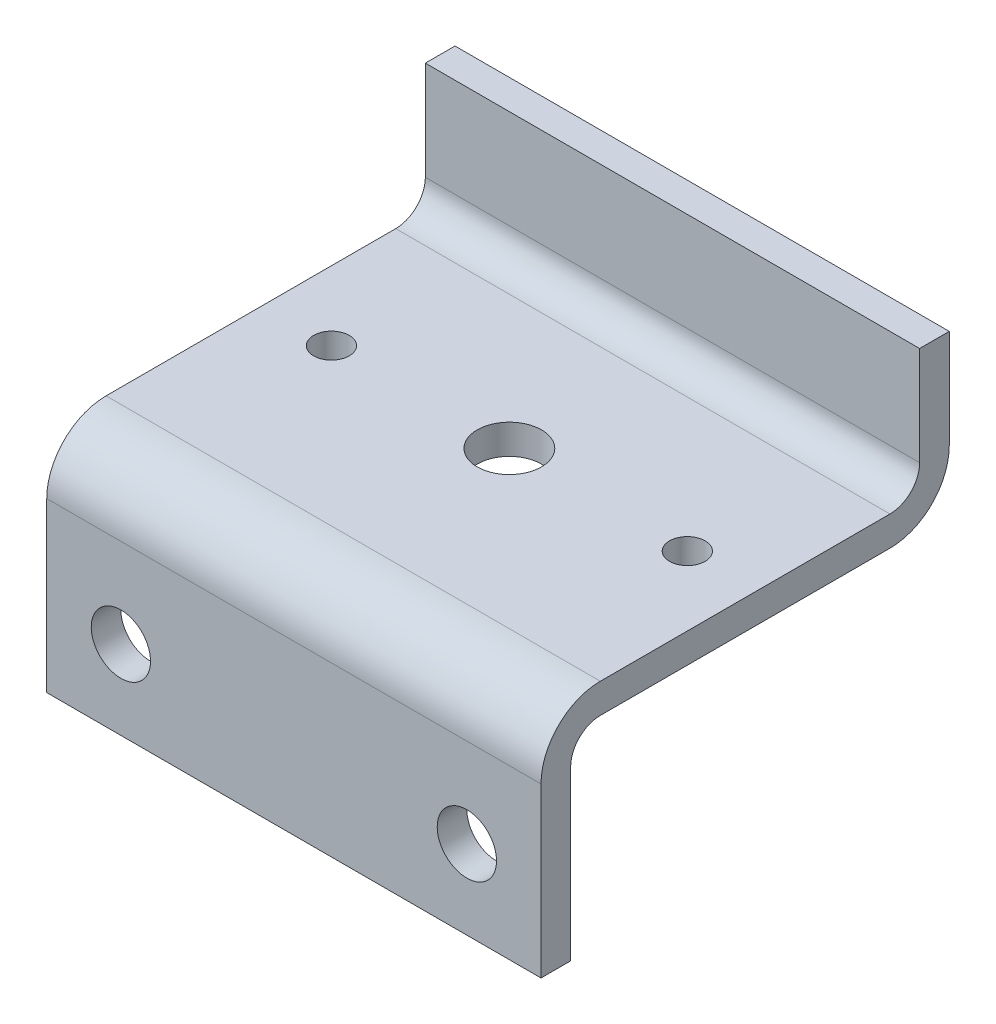
SolidWorks part; units mm, degrees
ref_plane "Front Plane" through (0, 0, 0) normal (0, 0, 1) x (1, 0, 0)
ref_plane "Top Plane" through (0, 0, 0) normal (0, 1, 0) x (1, 0, 0)
ref_plane "Right Plane" through (0, 0, 0) normal (1, 0, 0) x (0, 0, -1)
sketch "Sketch1" plane through (0, 0, 0) normal (1, 0, 0) x (0, 0, -1)
  line L0 (0, 0) -> (0, 17)
  line L1 (6, 23) -> (35.3, 23)
  line L4 (3, 17) -> (3, 0)
  line L5 (3, 0) -> (0, 0)
  line L6 (38.3, 26) -> (38.3, 36)
  line L7 (38.3, 36) -> (41.3, 36)
  line L8 (41.3, 36) -> (41.3, 26)
  line L9 (6, 20) -> (35.3, 20)
  arc A0 (6, 20) -> (3, 17) centre (6, 17) ccw
  arc A1 (0, 17) -> (6, 23) centre (6, 17) cw
  arc A2 (35.3, 23) -> (38.3, 26) centre (35.3, 26) ccw
  arc A3 (41.3, 26) -> (35.3, 20) centre (35.3, 26) cw
  point P11 (0, 23)
  point P16 (38.3, 23)
  dimension "D4" = 3
  dimension "D5" = 6
  dimension "D6" = 3
  dimension "D7" = 6
  dimension "D1" = 3
  dimension "D2" = 38.3
  dimension "D3" = 23
  dimension "D8" = 10
extrude "Boss-Extrude1" add sketch "Sketch1" along normal mid plane 50
sketch "Sketch2" plane through (0, 23, 0) normal (0, 1, 0) x (1, 0, 0)
  line L0 (-25, 21.8) -> (25, 21.8) construction
  line L1 (-25, 35.3) -> (-25, 6) construction
  line L2 (25, 35.3) -> (25, 6) construction
  line L4 (25, 41.3) -> (-25, 41.3) construction
  circle A0 centre (0, 21.8) radius 3.25
  circle A1 centre (-18, 21.8) radius 1.8
  circle A2 centre (18, 21.8) radius 1.8
  dimension "D1" = 6.5
  dimension "D2" = 3.6
  dimension "D3" = 18
  dimension "D4" = 36
  dimension "D5" = 19.5
extrude "Cut-Extrude1" cut sketch "Sketch2" against normal up to next
sketch "Sketch3" plane through (0, 0, -3) normal (0, 0, -1) x (-1, 0, 0)
  line L0 (17.5, 8) -> (-17.5, 8) construction
  line L1 (0, 0) -> (0, 17) construction
  line L2 (-25, 17) -> (25, 17) construction
  circle A0 centre (-17.5, 8) radius 3
  circle A1 centre (17.5, 8) radius 3
  point P3 (0, 8)
  dimension "D3" = 6
  dimension "D1" = 35
  dimension "D2" = 9
extrude "Cut-Extrude2" cut sketch "Sketch3" against normal up to next
